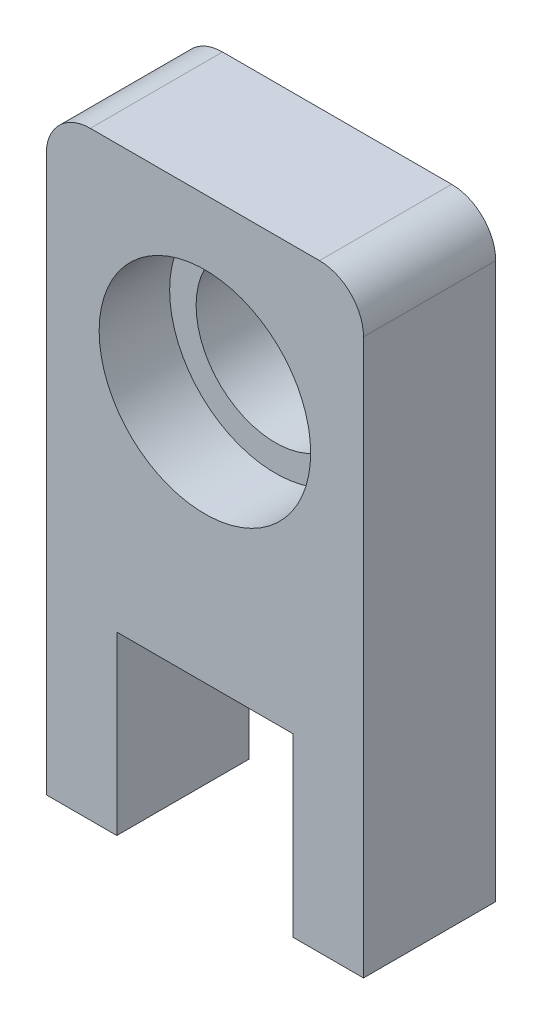
SolidWorks part; units mm, degrees
ref_plane "Alzado" through (0, 0, 0) normal (0, 0, 1) x (1, 0, 0)
ref_plane "Planta" through (0, 0, 0) normal (0, 1, 0) x (1, 0, 0)
ref_plane "Vista lateral" through (0, 0, 0) normal (1, 0, 0) x (0, 0, -1)
sketch "Croquis1" plane through (0, 0, 0) normal (0, 0, 1) x (1, 0, 0)
  line L0 (0, 0) -> (20, -20) construction
  line L1 (10, -10) -> (10, 28.6) construction
  line L2 (0, 0) -> (20, 0)
  line L3 (0, 0) -> (0, -20)
  line L4 (0, -20) -> (20, -20)
  line L5 (20, 0) -> (20, -20)
  line L6 (28, -20) -> (-8, -20)
  line L7 (10, -20) -> (10, 48) construction
  line L8 (23, 48) -> (-3, 48)
  line L9 (-8, 43) -> (-8, -20)
  line L12 (28, 43) -> (28, -20)
  circle A0 centre (10, 28.6) radius 12
  arc A1 (28, 43) -> (23, 48) centre (23, 43) ccw
  arc A2 (-3, 48) -> (-8, 43) centre (-3, 43) ccw
  point P14 (10, -20)
  point P17 (28, 48)
  point P20 (-8, 48)
  dimension "D2" = 24
  dimension "D3" = 18
  dimension "D6" = 5
  dimension "D1" = 20
  dimension "D4" = 18
  dimension "D5" = 28.6
  dimension "D7" = 68
extrude "Saliente-Extruir1" add sketch "Croquis1" along normal blind 15 contours L8 A2 L9 L6 L3 L2 L5 L12 A1 A0
sketch "Croquis3" plane through (0, 0, 0) normal (0, 0, -1) x (-1, 0, 0)
  circle A0 centre (-10, 28.6) radius 12
  circle A1 centre (-10, 28.6) radius 9
  dimension "D1" = 3
extrude "Saliente-Extruir2" add sketch "Croquis3" against normal blind 7
